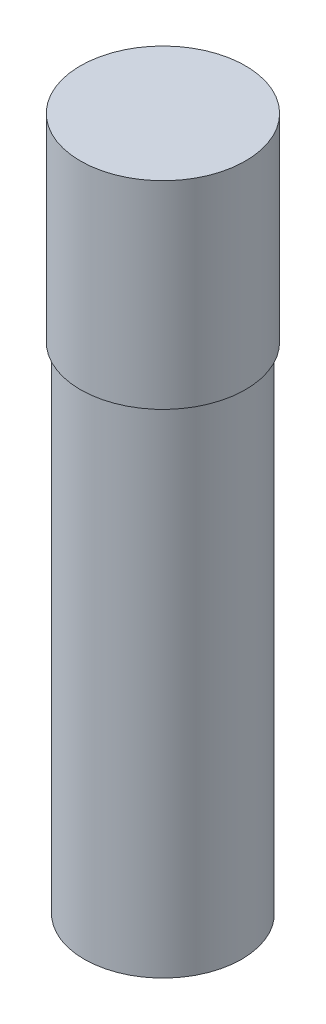
SolidWorks part; units mm, degrees
ref_plane "Alzado" through (0, 0, 0) normal (0, 0, 1) x (1, 0, 0)
ref_plane "Planta" through (0, 0, 0) normal (0, 1, 0) x (1, 0, 0)
ref_plane "Vista lateral" through (0, 0, 0) normal (1, 0, 0) x (0, 0, -1)
sketch "Croquis2" plane through (0, 0, 0) normal (0, 1, 0) x (1, 0, 0)
  circle A0 centre (0, 0) radius 4.775
  dimension "D1" = 9.55
extrude "Saliente-Extruir1" add sketch "Croquis2" along normal blind 30
sketch "Croquis3" plane through (0, 30, 0) normal (0, 1, 0) x (1, 0, 0)
  circle A0 centre (0, 0) radius 5
  dimension "D1" = 10
extrude "Saliente-Extruir2" add sketch "Croquis3" along normal blind 12
